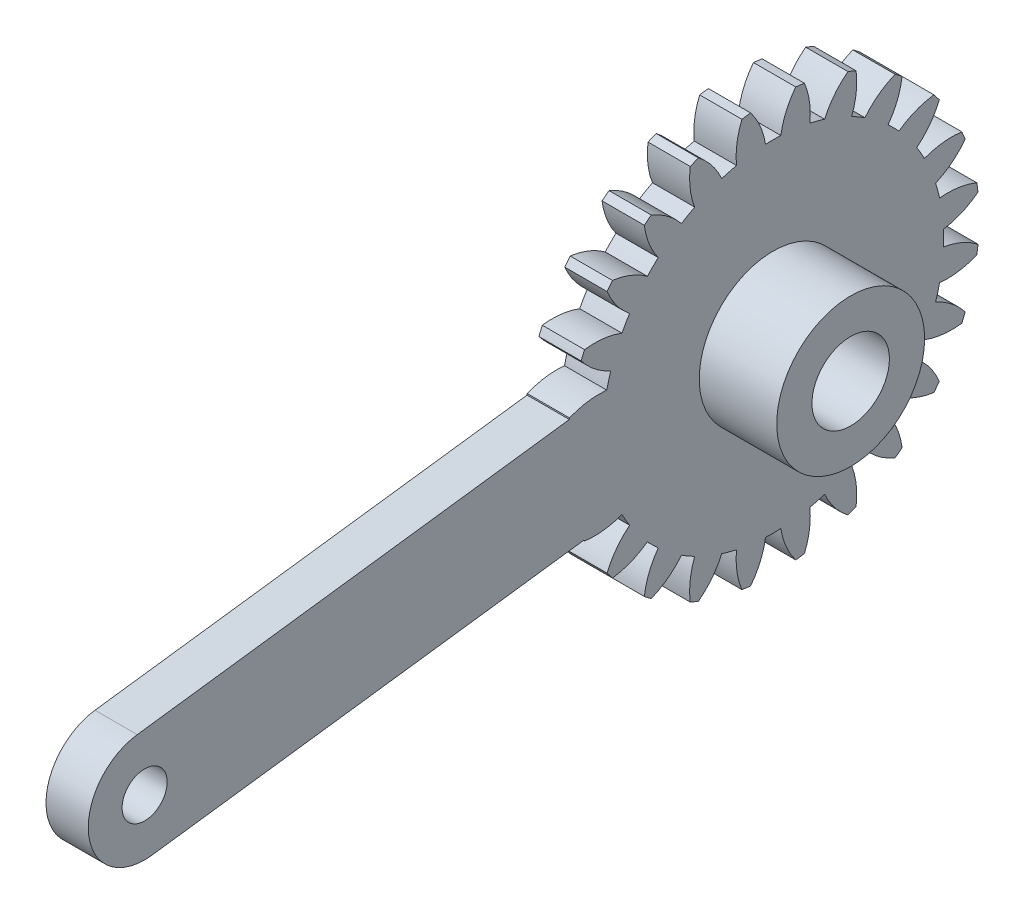
SolidWorks part; units mm, degrees
ref_plane "Front Plane" through (0, 0, 0) normal (0, 0, 1) x (1, 0, 0)
ref_plane "Top Plane" through (0, 0, 0) normal (0, 1, 0) x (1, 0, 0)
ref_plane "Right Plane" through (0, 0, 0) normal (1, 0, 0) x (0, 0, -1)
ref_plane "Plane1" through (3, 0, 0) normal (1, 0, 0) x (0, 0, -1)
sketch "Sketch1" plane through (3, 0, 0) normal (1, 0, 0) x (0, 0, -1)
  circle A0 centre (0, 0) radius 1.5
  arc A1 (-14.5373, 1.5991) -> (-12.0806, 0.5427) centre (-11.2423, 5.8773) ccw
  arc A2 (-12.0806, 0.5427) -> (-12.0806, -0.5427) centre (0, 0) ccw
  arc A3 (-12.0806, -0.5427) -> (-14.5373, -1.5991) centre (-11.2423, -5.8773) ccw
  arc A4 (-14.5373, -1.5991) -> (-14.4558, -2.2179) centre (0, 0) ccw
  arc A5 (-14.4558, -2.2179) -> (-11.8094, -2.6025) centre (-12.3803, 2.7673) ccw
  arc A6 (-11.8094, -2.6025) -> (-11.5285, -3.6509) centre (0, 0) ccw
  arc A7 (-11.5285, -3.6509) -> (-13.6281, -5.3071) centre (-9.3381, -8.5867) ccw
  arc A8 (-13.6281, -5.3071) -> (-13.3892, -5.8838) centre (0, 0) ccw
  arc A9 (-13.3892, -5.8838) -> (-10.7334, -5.5703) centre (-12.6747, -0.5313) ccw
  arc A10 (-10.7334, -5.5703) -> (-10.1907, -6.5103) centre (0, 0) ccw
  arc A11 (-10.1907, -6.5103) -> (-11.7901, -8.6535) centre (-6.7975, -10.711) ccw
  arc A12 (-11.7901, -8.6535) -> (-11.4102, -9.1487) centre (0, 0) ccw
  arc A13 (-11.4102, -9.1487) -> (-8.926, -8.1585) centre (-12.1053, -3.7936) ccw
  arc A14 (-8.926, -8.1585) -> (-8.1585, -8.926) centre (0, 0) ccw
  arc A15 (-8.1585, -8.926) -> (-9.1487, -11.4102) centre (-3.7936, -12.1053) ccw
  arc A16 (-9.1487, -11.4102) -> (-8.6535, -11.7901) centre (0, 0) ccw
  arc A17 (-8.6535, -11.7901) -> (-6.5103, -10.1907) centre (-10.711, -6.7975) ccw
  arc A18 (-6.5103, -10.1907) -> (-5.5703, -10.7334) centre (0, 0) ccw
  arc A19 (-5.5703, -10.7334) -> (-5.8838, -13.3892) centre (-0.5313, -12.6747) ccw
  arc A20 (-5.8838, -13.3892) -> (-5.3071, -13.6281) centre (0, 0) ccw
  arc A21 (-5.3071, -13.6281) -> (-3.6509, -11.5285) centre (-8.5867, -9.3381) ccw
  arc A22 (-3.6509, -11.5285) -> (-2.6025, -11.8094) centre (0, 0) ccw
  arc A23 (-2.6025, -11.8094) -> (-2.2179, -14.4558) centre (2.7673, -12.3803) ccw
  arc A24 (-2.2179, -14.4558) -> (-1.5991, -14.5373) centre (0, 0) ccw
  arc A25 (-1.5991, -14.5373) -> (-0.5427, -12.0806) centre (-5.8773, -11.2423) ccw
  arc A26 (-0.5427, -12.0806) -> (0.5427, -12.0806) centre (0, 0) ccw
  arc A27 (0.5427, -12.0806) -> (1.5991, -14.5373) centre (5.8773, -11.2423) ccw
  arc A28 (1.5991, -14.5373) -> (2.2179, -14.4558) centre (0, 0) ccw
  arc A29 (2.2179, -14.4558) -> (2.6025, -11.8094) centre (-2.7673, -12.3803) ccw
  arc A30 (2.6025, -11.8094) -> (3.6509, -11.5285) centre (0, 0) ccw
  arc A31 (3.6509, -11.5285) -> (5.3071, -13.6281) centre (8.5867, -9.3381) ccw
  arc A32 (5.3071, -13.6281) -> (5.8838, -13.3892) centre (0, 0) ccw
  arc A33 (5.8838, -13.3892) -> (5.5703, -10.7334) centre (0.5313, -12.6747) ccw
  arc A34 (5.5703, -10.7334) -> (6.5103, -10.1907) centre (0, 0) ccw
  arc A35 (6.5103, -10.1907) -> (8.6535, -11.7901) centre (10.711, -6.7975) ccw
  arc A36 (8.6535, -11.7901) -> (9.1487, -11.4102) centre (0, 0) ccw
  arc A37 (9.1487, -11.4102) -> (8.1585, -8.926) centre (3.7936, -12.1053) ccw
  arc A38 (8.1585, -8.926) -> (8.926, -8.1585) centre (0, 0) ccw
  arc A39 (8.926, -8.1585) -> (11.4102, -9.1487) centre (12.1053, -3.7936) ccw
  arc A40 (11.4102, -9.1487) -> (11.7901, -8.6535) centre (0, 0) ccw
  arc A41 (11.7901, -8.6535) -> (10.1907, -6.5103) centre (6.7975, -10.711) ccw
  arc A42 (10.1907, -6.5103) -> (10.7334, -5.5703) centre (0, 0) ccw
  arc A43 (10.7334, -5.5703) -> (13.3892, -5.8838) centre (12.6747, -0.5313) ccw
  arc A44 (13.3892, -5.8838) -> (13.6281, -5.3071) centre (0, 0) ccw
  arc A45 (13.6281, -5.3071) -> (11.5285, -3.6509) centre (9.3381, -8.5867) ccw
  arc A46 (11.5285, -3.6509) -> (11.8094, -2.6025) centre (0, 0) ccw
  arc A47 (11.8094, -2.6025) -> (14.4558, -2.2179) centre (12.3803, 2.7673) ccw
  arc A48 (14.4558, -2.2179) -> (14.5373, -1.5991) centre (0, 0) ccw
  arc A49 (14.5373, -1.5991) -> (12.0806, -0.5427) centre (11.2423, -5.8773) ccw
  arc A50 (12.0806, -0.5427) -> (12.0806, 0.5427) centre (0, 0) ccw
  arc A51 (12.0806, 0.5427) -> (14.5373, 1.5991) centre (11.2423, 5.8773) ccw
  arc A52 (14.5373, 1.5991) -> (14.4558, 2.2179) centre (0, 0) ccw
  arc A53 (14.4558, 2.2179) -> (11.8094, 2.6025) centre (12.3803, -2.7673) ccw
  arc A54 (11.8094, 2.6025) -> (11.5285, 3.6509) centre (0, 0) ccw
  arc A55 (11.5285, 3.6509) -> (13.6281, 5.3071) centre (9.3381, 8.5867) ccw
  arc A56 (13.6281, 5.3071) -> (13.3892, 5.8838) centre (0, 0) ccw
  arc A57 (13.3892, 5.8838) -> (10.7334, 5.5703) centre (12.6747, 0.5313) ccw
  arc A58 (10.7334, 5.5703) -> (10.1907, 6.5103) centre (0, 0) ccw
  arc A59 (10.1907, 6.5103) -> (11.7901, 8.6535) centre (6.7975, 10.711) ccw
  arc A60 (11.7901, 8.6535) -> (11.4102, 9.1487) centre (0, 0) ccw
  arc A61 (11.4102, 9.1487) -> (8.926, 8.1585) centre (12.1053, 3.7936) ccw
  arc A62 (8.926, 8.1585) -> (8.1585, 8.926) centre (0, 0) ccw
  arc A63 (8.1585, 8.926) -> (9.1487, 11.4102) centre (3.7936, 12.1053) ccw
  arc A64 (9.1487, 11.4102) -> (8.6535, 11.7901) centre (0, 0) ccw
  arc A65 (8.6535, 11.7901) -> (6.5103, 10.1907) centre (10.711, 6.7975) ccw
  arc A66 (6.5103, 10.1907) -> (5.5703, 10.7334) centre (0, 0) ccw
  arc A67 (5.5703, 10.7334) -> (5.8838, 13.3892) centre (0.5313, 12.6747) ccw
  arc A68 (5.8838, 13.3892) -> (5.3071, 13.6281) centre (0, 0) ccw
  arc A69 (5.3071, 13.6281) -> (3.6509, 11.5285) centre (8.5867, 9.3381) ccw
  arc A70 (3.6509, 11.5285) -> (2.6025, 11.8094) centre (0, 0) ccw
  arc A71 (2.6025, 11.8094) -> (2.2179, 14.4558) centre (-2.7673, 12.3803) ccw
  arc A72 (2.2179, 14.4558) -> (1.5991, 14.5373) centre (0, 0) ccw
  arc A73 (1.5991, 14.5373) -> (0.5427, 12.0806) centre (5.8773, 11.2423) ccw
  arc A74 (0.5427, 12.0806) -> (-0.5427, 12.0806) centre (0, 0) ccw
  arc A75 (-0.5427, 12.0806) -> (-1.5991, 14.5373) centre (-5.8773, 11.2423) ccw
  arc A76 (-1.5991, 14.5373) -> (-2.2179, 14.4558) centre (0, 0) ccw
  arc A77 (-2.2179, 14.4558) -> (-2.6025, 11.8094) centre (2.7673, 12.3803) ccw
  arc A78 (-2.6025, 11.8094) -> (-3.6509, 11.5285) centre (0, 0) ccw
  arc A79 (-3.6509, 11.5285) -> (-5.3071, 13.6281) centre (-8.5867, 9.3381) ccw
  arc A80 (-5.3071, 13.6281) -> (-5.8838, 13.3892) centre (0, 0) ccw
  arc A81 (-5.8838, 13.3892) -> (-5.5703, 10.7334) centre (-0.5313, 12.6747) ccw
  arc A82 (-5.5703, 10.7334) -> (-6.5103, 10.1907) centre (0, 0) ccw
  arc A83 (-6.5103, 10.1907) -> (-8.6535, 11.7901) centre (-10.711, 6.7975) ccw
  arc A84 (-8.6535, 11.7901) -> (-9.1487, 11.4102) centre (0, 0) ccw
  arc A85 (-9.1487, 11.4102) -> (-8.1585, 8.926) centre (-3.7936, 12.1053) ccw
  arc A86 (-8.1585, 8.926) -> (-8.926, 8.1585) centre (0, 0) ccw
  arc A87 (-8.926, 8.1585) -> (-11.4102, 9.1487) centre (-12.1053, 3.7936) ccw
  arc A88 (-11.4102, 9.1487) -> (-11.7901, 8.6535) centre (0, 0) ccw
  arc A89 (-11.7901, 8.6535) -> (-10.1907, 6.5103) centre (-6.7975, 10.711) ccw
  arc A90 (-10.1907, 6.5103) -> (-10.7334, 5.5703) centre (0, 0) ccw
  arc A91 (-10.7334, 5.5703) -> (-13.3892, 5.8838) centre (-12.6747, 0.5313) ccw
  arc A92 (-13.3892, 5.8838) -> (-13.6281, 5.3071) centre (0, 0) ccw
  arc A93 (-13.6281, 5.3071) -> (-11.5285, 3.6509) centre (-9.3381, 8.5867) ccw
  arc A94 (-11.5285, 3.6509) -> (-11.8094, 2.6025) centre (0, 0) ccw
  arc A95 (-11.8094, 2.6025) -> (-14.4558, 2.2179) centre (-12.3803, -2.7673) ccw
  arc A96 (-14.4558, 2.2179) -> (-14.5373, 1.5991) centre (0, 0) ccw
extrude "Boss-Extrude1" add sketch "Sketch1" against normal blind 3
sketch "Sketch2" plane through (3, 0, 0) normal (1, 0, 0) x (0, 0, -1)
  line L0 (0, 0) -> (-44.615, -5.8737) construction
  line L1 (0.5221, -3.9658) -> (-44.0929, -9.8395)
  line L2 (0, 0) -> (-66.8826, 0) construction
  line L3 (-0.5221, 3.9658) -> (-45.1371, -1.9079)
  arc A0 (0.5221, -3.9658) -> (-0.5221, 3.9658) centre (0, 0) ccw
  arc A1 (-45.1371, -1.9079) -> (-44.0929, -9.8395) centre (-44.615, -5.8737) ccw
  circle A2 centre (-44.615, -5.8737) radius 1.6
  circle A3 centre (0, 0) radius 1.5
  point P2 (-22.3075, -2.9368)
  dimension "D2" = 4
  dimension "D3" = 7.5
  dimension "D5" = 3.2
  dimension "D1" = 45
extrude "Boss-Extrude2" add sketch "Sketch2" against normal blind 3
sketch "Sketch3" plane through (3, 0, 0) normal (1, 0, 0) x (0, 0, -1)
  circle A0 centre (0, 0) radius 5.25
  circle A1 centre (0, 0) radius 2.75
  dimension "D1" = 2.5
  dimension "D2" = 5.5
extrude "Boss-Extrude3" add sketch "Sketch3" along normal blind 5.5
sketch "Sketch4" plane through (3, 0, 0) normal (1, 0, 0) x (0, 0, -1)
  circle A0 centre (0, 0) radius 2.75
extrude "Cut-Extrude1" cut sketch "Sketch4" against normal blind 2
